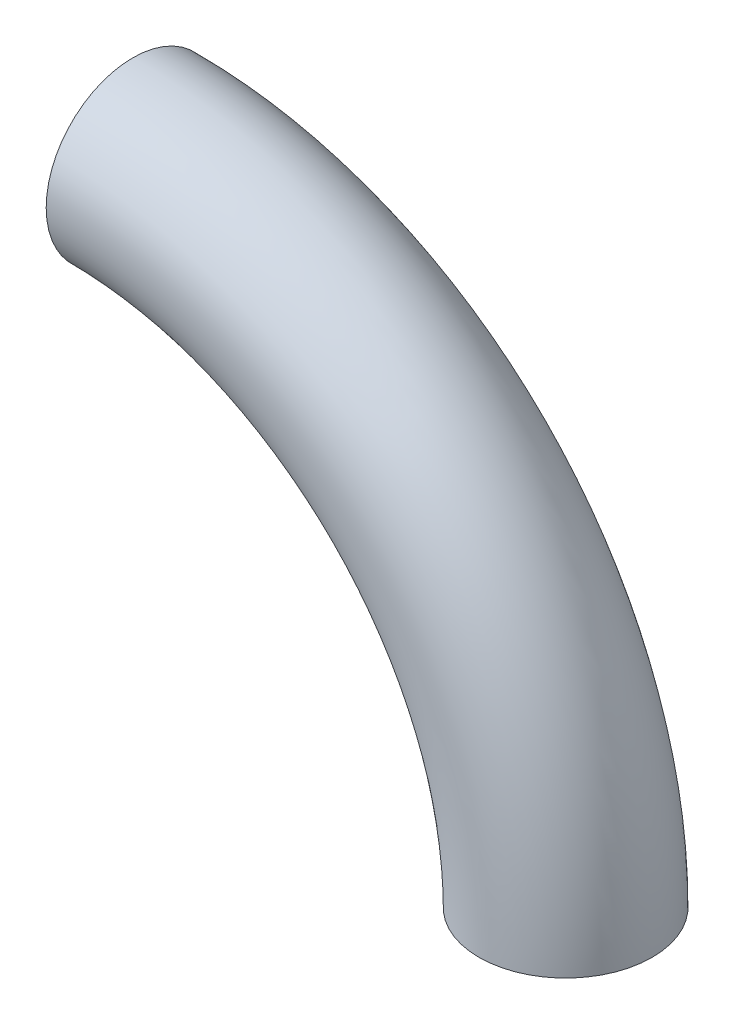
SolidWorks part; units mm, degrees
ref_plane "Front Plane" through (0, 0, 0) normal (0, 0, 1) x (1, 0, 0)
ref_plane "Top Plane" through (0, 0, 0) normal (0, 1, 0) x (1, 0, 0)
ref_plane "Right Plane" through (0, 0, 0) normal (1, 0, 0) x (0, 0, -1)
ref_plane "plane:profile" through (0, 0, 0) normal (0, -1, 0) x (1, 0, 0)
sketch "sketch:profile" plane through (0, 0, 0) normal (0, -1, 0) x (1, 0, 0)
  line L0 (0, -15) -> (0, 15) construction
  circle A0 centre (20, 0) radius 4
revolve "feature:torus" add sketch "sketch:profile" angle 90 about L0
